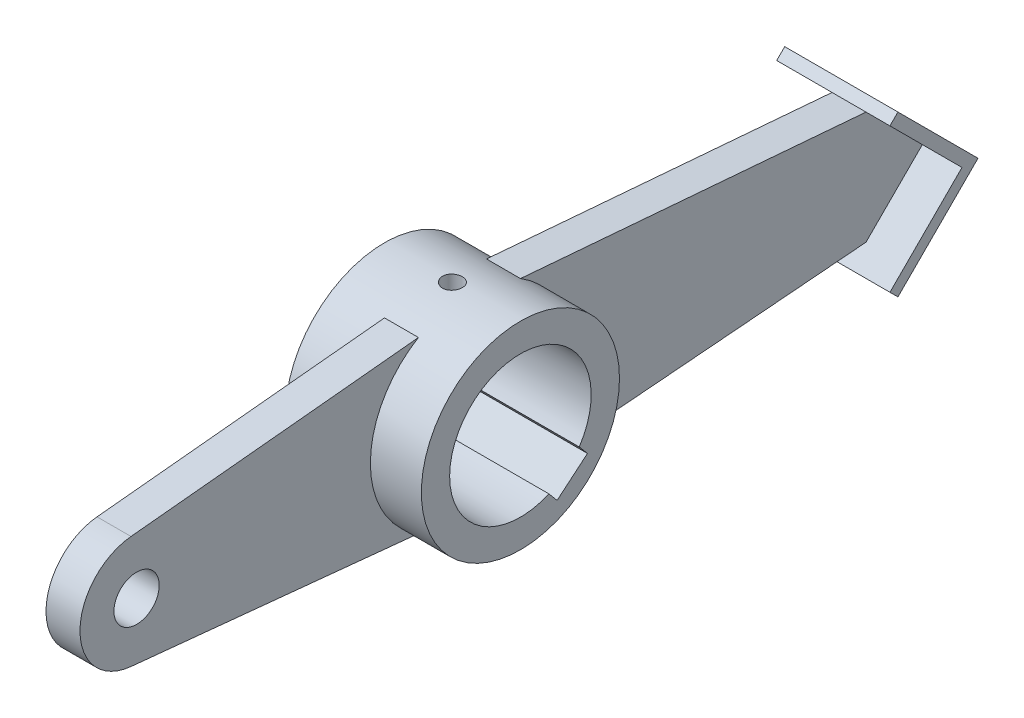
SolidWorks part; units mm, degrees
material "ASTM A36"
ref_plane "Front Plane" through (0, 0, 0) normal (0, 0, 1) x (1, 0, 0)
ref_plane "Top Plane" through (0, 0, 0) normal (0, 1, 0) x (1, 0, 0)
ref_plane "Right Plane" through (0, 0, 0) normal (1, 0, 0) x (0, 0, -1)
sketch "Sketch1" plane through (0, 0, 0) normal (1, 0, 0) x (0, 0, -1)
  circle A0 centre (0, 0) radius 25
  circle A1 centre (0, 0) radius 35
  dimension "D1" = 50
  dimension "D2" = 70
extrude "Boss-Extrude1" add sketch "Sketch1" along normal mid plane 48
sketch "Sketch2" plane through (0, 0, 0) normal (1, 0, 0) x (0, 0, -1)
  line L0 (-18.0278, 30) -> (-119.579, 19.9018)
  line L1 (-119.579, -19.9018) -> (-18.0278, -30)
  line L2 (0, 26.4) -> (0, -26.4) construction
  line L3 (140.0982, -19.9018) -> (18.0278, -30)
  line L4 (18.0278, 30) -> (140.0982, 19.9018)
  line L5 (0, 0) -> (206.5979, 0) construction
  line L6 (140.0982, 19.9018) -> (160, 0)
  line L7 (160, 0) -> (140.0982, -19.9018)
  circle A0 centre (0, 0) radius 35 construction
  arc A1 (-119.579, 19.9018) -> (-119.579, -19.9018) centre (-117.6, 0) ccw
  arc A2 (18.0278, 30) -> (18.0278, -30) centre (0, 0) cw
  circle A3 centre (0, 0) radius 35
  arc A4 (-18.0278, 30) -> (-18.0278, -30) centre (0, 0) ccw
  dimension "D2" = 20
  dimension "D1" = 117.6
  dimension "D3" = 60
  dimension "D5" = 160
  dimension "D4" = 0
extrude "Boss-Extrude2" add sketch "Sketch2" along normal mid plane 12
sketch "Sketch3" plane through (6, 0, 0) normal (1, 0, 0) x (0, 0, -1)
  circle A0 centre (-117.6, 0) radius 8
  dimension "D1" = 16
extrude "Cut-Extrude1" cut sketch "Sketch3" against normal blind 15
sketch "Sketch5" plane through (24, 0, 0) normal (1, 0, 0) x (0, 0, -1)
  line L0 (0, 0) -> (19.4876, -23.2245) construction
  line L1 (23.6818, -17.3328) -> (12.9571, -26.3318)
  line L2 (12.9571, -26.3318) -> (3.998, -15.6546)
  line L3 (3.998, -15.6546) -> (14.7226, -6.6556)
  line L4 (14.7226, -6.6556) -> (23.6818, -17.3328)
  line L5 (0, 0) -> (19.9004, 0) construction
  point P4 (18.3194, -21.8323)
  dimension "D1" = 310
  dimension "D2" = 14
  dimension "D3" = 28.5
extrude "Cut-Extrude2" cut sketch "Sketch5" against normal through all
ref_plane "Plane1" through (0, 35, 0) normal (0, 1, 0) x (-1, 0, 0)
sketch "Sketch6" plane through (0, 35, 0) normal (0, 1, 0) x (-1, 0, 0)
  circle A0 centre (0, 0) radius 3.5
  dimension "D1" = 7
extrude "Cut-Extrude3" cut sketch "Sketch6" against normal blind 24
ref_plane "Plane2" through (11, 0, 0) normal (1, 0, 0) x (0, 0, -1)
sketch "Sketch11" plane through (0, 0, 0) normal (1, 0, 0) x (0, 0, -1)
  line L0 (134.5442, -25.4558) -> (160, 0)
  line L1 (160, 0) -> (134.5442, 25.4558)
  line L2 (134.5442, 25.4558) -> (137.3726, 28.2843)
  line L3 (137.3726, 28.2843) -> (165.6569, 0)
  line L4 (165.6569, 0) -> (137.3726, -28.2843)
  line L5 (137.3726, -28.2843) -> (134.5442, -25.4558)
  line L7 (140.0982, 19.9018) -> (160, 0) construction
  dimension "D1" = 40
  dimension "D2" = 40
  dimension "D3" = 4
  dimension "D4" = 4
extrude "Boss-Extrude4" add sketch "Sketch11" along normal mid plane 40 separate body
